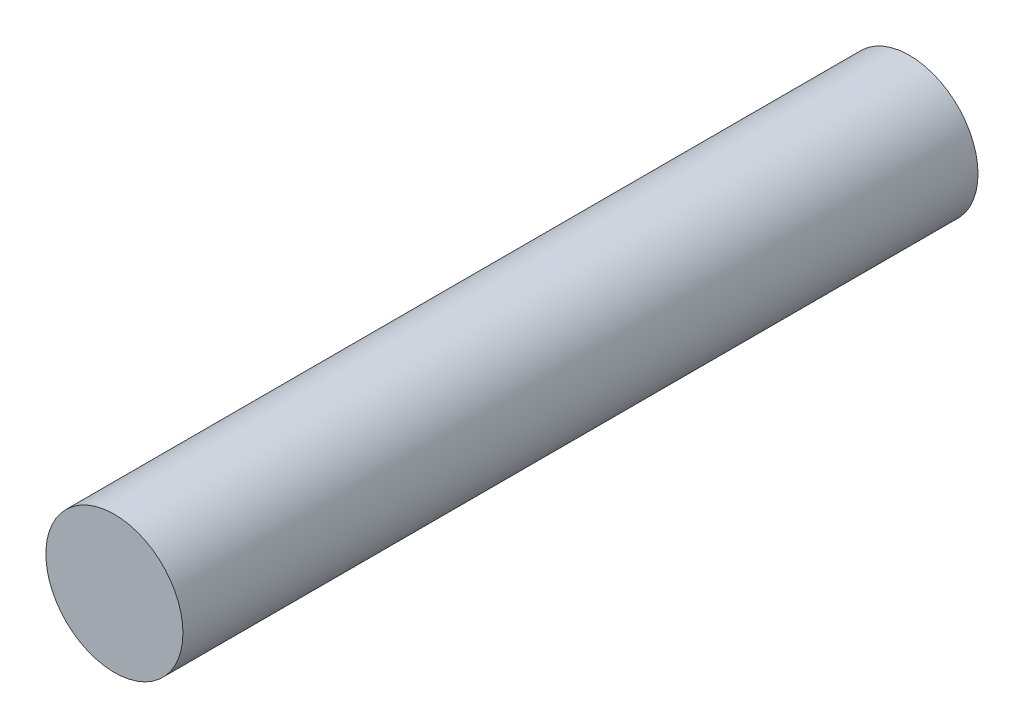
SolidWorks part; units mm, degrees
ref_plane "Front Plane" through (0, 0, 0) normal (0, 0, 1) x (1, 0, 0)
ref_plane "Top Plane" through (0, 0, 0) normal (0, 1, 0) x (1, 0, 0)
ref_plane "Right Plane" through (0, 0, 0) normal (1, 0, 0) x (0, 0, -1)
sketch "Sketch1" plane through (0, 0, 0) normal (0, 0, 1) x (1, 0, 0)
  circle A0 centre (0, 0) radius 3.175
  dimension "D1" = 6.35
extrude "Boss-Extrude1" add sketch "Sketch1" along normal blind 36.83
equation "\"Wheel Thickness\"= 1in"
equation "\"Wheel Diameter\"= 3in"
equation "\"Motor Rear Diameter\" = 36.2mm"
equation "\"Motor Front Diameter\" = 12mm"
equation "\"Material Thickness\" = .25in"
equation "\"Wheel Cutout Diameter\"= 2cm"
equation "\"Motor Mount Tab Thickness\" = 100mm"
equation "\"Motor Mount Tab Height\" = 40mm"
equation "\"Motor Shaft Diameter\" = 3mm"
equation "\"Wheel Radius Clearance\" = 5mm"
equation "\"Wheel Cutout Width\" = 1.5in"
equation "\"Base Diameter\" = 10in"
equation "\"Wheel Mount Distance\" = 5mm"
equation "\"Motor Mount Distance\" = 50mm"
equation "\"Motor Cutout Length\" = 6in"
equation "\"Motor Cutout Height\" = 2in "
equation "\"Rod Diameter\" = 3/8in"
equation "\"Rod Length\" = 1.5in"
equation "\"Barrel Front Length\" = 1.8in"
equation "\"Barrerl Rear Length\" = 5in "
equation "\"Barrel Fillet Radius\" = 1in "
equation "\"Barrel Angle\" = 20deg"
equation "\"Barrel Diameter\" = 50mm"
equation "\"Barrel Shell Width\" = 2mm"
equation "\"Second Level Diameter\" = 10in"
equation "\"Ball Diameter\" = 40mm"
equation "\"Third Level Length\" = 9in"
equation "\"Third Level Height\" = 9in"
equation "\"Barrel Tab Clearance\" = 5mm"
equation "\"Barrel Tab Distance Away\" = 2mm"
equation "\"Hole Distance Apart\" = 2.8in"
equation "\"Barrel Tab Distance\"= 1.5in "
equation "\"Third Level Rod Distance\" = .5in"
equation " \"Second Rod Diameter\" = 3/8in"
equation "\"Second Rod Length\" = 3.88in"
equation "\"Bumper Wheel Clearance\" = 1.2in"
equation "\"Servo Tab Height\" = 4in"
equation "\"Servo Tab Width\" = 2in"
equation "\"Servo Tab Hole Horizontal Distance\" = 1in"
equation "\"Servo Tab Hole Vertical Distance\" = 1.5in "
equation "\"Servo Hole Vertical Distance\" = 3in"
equation "\"Servo Hole Diameter\" = 1/4in"
equation "\"Servo Hole Shaft Length\" = 1.45in"
equation "\"D1@Boss-Extrude1\"=\"Servo Hole Shaft Length\""
